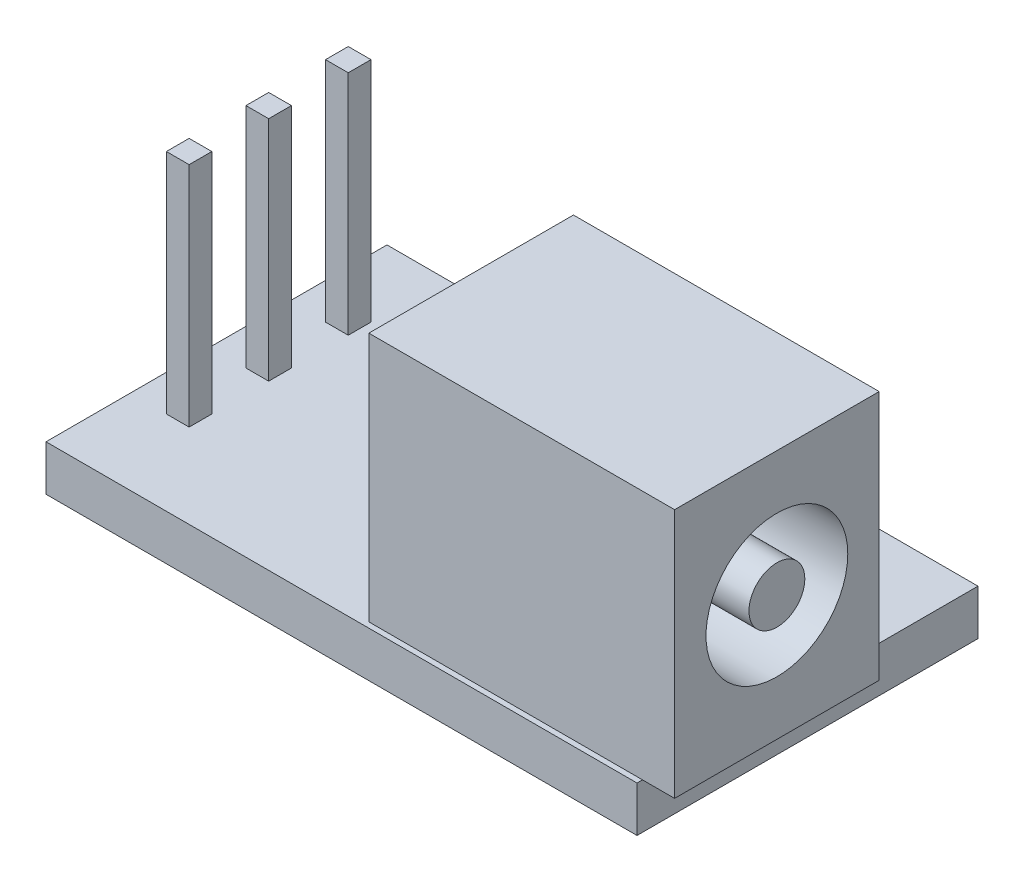
SolidWorks part; units mm, degrees
ref_plane "Front Plane" through (0, 0, 0) normal (0, 0, 1) x (1, 0, 0)
ref_plane "Top Plane" through (0, 0, 0) normal (0, 1, 0) x (1, 0, 0)
ref_plane "Right Plane" through (0, 0, 0) normal (1, 0, 0) x (0, 0, -1)
sketch "Sketch1" plane through (0, 0, 0) normal (0, 1, 0) x (1, 0, 0)
  line L1 (-13, 7.5) -> (13, 7.5)
  line L2 (-13, 7.5) -> (-13, -7.5)
  line L3 (-13, -7.5) -> (13, -7.5)
  line L4 (13, 7.5) -> (13, -7.5)
  line L5 (-13, 7.5) -> (13, -7.5) construction
  line L6 (-13, -7.5) -> (13, 7.5) construction
  point P0 (0, 0)
  dimension "D1" = 15
  dimension "D2" = 26
extrude "Boss-Extrude1" add sketch "Sketch1" along normal blind 2
sketch "Sketch2" plane through (0, 2, 0) normal (0, 1, 0) x (1, 0, 0)
  line L1 (0.9626, 1.7401) -> (14.4128, 1.7401)
  line L2 (0.9626, 1.7401) -> (0.9626, -7.2599)
  line L3 (0.9626, -7.2599) -> (14.4128, -7.2599)
  line L4 (14.4128, 1.7401) -> (14.4128, -7.2599)
  dimension "D1" = 9
extrude "Boss-Extrude2" add sketch "Sketch2" along normal blind 11
sketch "Sketch3" plane through (0, 2, 0) normal (0, 1, 0) x (1, 0, 0)
  line L0 (-13, 7.5) -> (-13, -7.5) construction
  circle A0 centre (-4, 0) radius 1.5
  point P5 (-13, 0)
  dimension "D2" = 3
  dimension "D1" = 9
extrude "Cut-Extrude1" cut sketch "Sketch3" against normal blind 11
sketch "Sketch4" plane through (0, 2, 0) normal (0, 1, 0) x (1, 0, 0)
  line L1 (-11.4106, -3.7934) -> (-10.4106, -3.7934)
  line L2 (-11.4106, -3.7934) -> (-11.4106, -2.7934)
  line L3 (-11.4106, -2.7934) -> (-10.4106, -2.7934)
  line L4 (-10.4106, -3.7934) -> (-10.4106, -2.7934)
  line L5 (-11.4106, -0.2934) -> (-10.4106, -0.2934)
  line L6 (-11.4106, -0.2934) -> (-11.4106, 0.7066)
  line L7 (-11.4106, 0.7066) -> (-10.4106, 0.7066)
  line L8 (-10.4106, -0.2934) -> (-10.4106, 0.7066)
  line L9 (-11.4106, 3.2066) -> (-10.4106, 3.2066)
  line L10 (-11.4106, 3.2066) -> (-11.4106, 4.2066)
  line L11 (-11.4106, 4.2066) -> (-10.4106, 4.2066)
  line L12 (-10.4106, 3.2066) -> (-10.4106, 4.2066)
  dimension "D1" = 1
  dimension "D2" = 1
  dimension "D3" = 2.5
  dimension "D4" = 2.5
extrude "Boss-Extrude3" add sketch "Sketch4" along normal blind 10
sketch "Sketch5" plane through (14.4128, 0, 0) normal (1, 0, 0) x (0, 0, -1)
  line L0 (-2.7599, 2) -> (-2.7599, 10.1502) construction
  line L1 (-7.2599, 2) -> (1.7401, 2) construction
  line L2 (-7.2599, 7.5) -> (1.1445, 7.5) construction
  line L3 (-7.2599, 13) -> (-7.2599, 2) construction
  circle A0 centre (-2.7599, 7.5) radius 3.1184
  circle A2 centre (-2.7599, 7.5) radius 1.229
extrude "Cut-Extrude2" cut sketch "Sketch5" against normal blind 10
